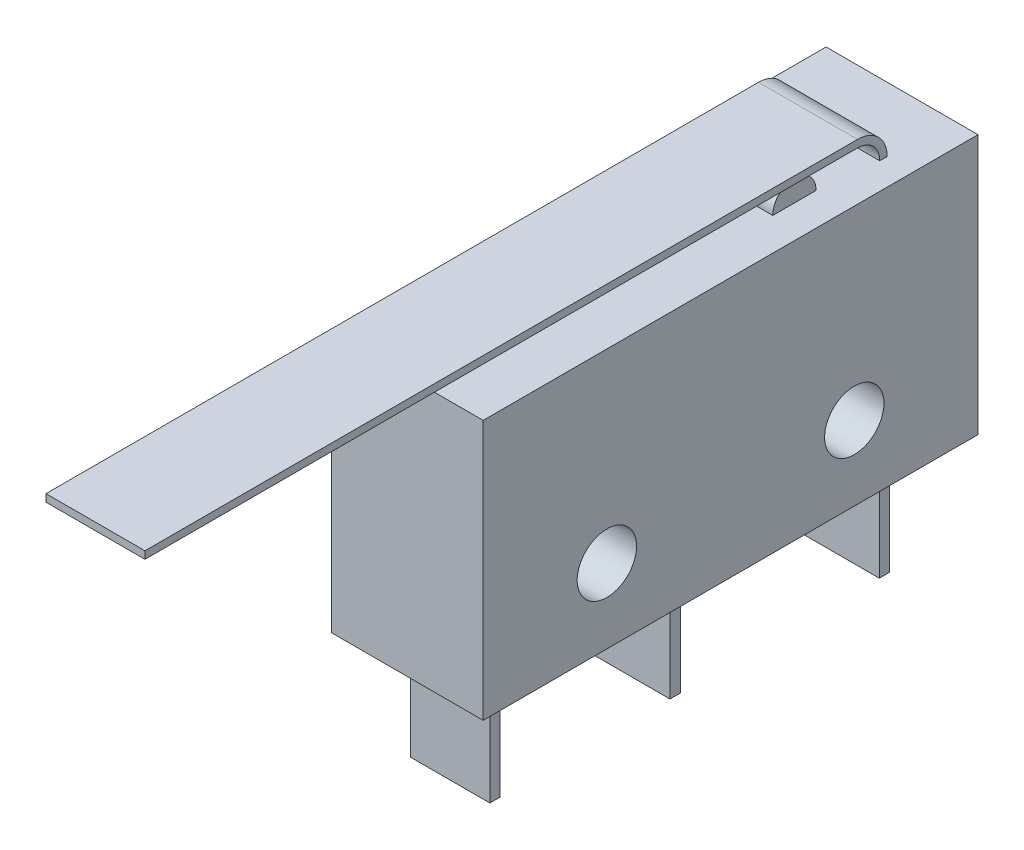
SolidWorks part; units mm, degrees
ref_plane "Front Plane" through (0, 0, 0) normal (0, 0, 1) x (1, 0, 0)
ref_plane "Top Plane" through (0, 0, 0) normal (0, 1, 0) x (1, 0, 0)
ref_plane "Right Plane" through (0, 0, 0) normal (1, 0, 0) x (0, 0, -1)
sketch "Sketch1" plane through (0, 0, 0) normal (1, 0, 0) x (0, 0, -1)
  line L1 (0, 0) -> (20, 0)
  line L2 (0, 0) -> (0, -10.5)
  line L3 (0, -10.5) -> (20, -10.5)
  line L4 (20, 0) -> (20, -10.5)
  circle A0 centre (5, -7.5) radius 1.2
  circle A1 centre (15, -7.5) radius 1.2
  circle A2 centre (5, -7.5) radius 1.2 construction
  circle A3 centre (15, -7.5) radius 1.2 construction
extrude "Boss-Extrude1" add sketch "Sketch1" along normal blind 6.14
ref_plane "Midplane" through (3.07, 0, 0) normal (1, 0, 0) x (0, 0, -1)
sketch "Sketch2" plane through (3.07, 0, 0) normal (1, 0, 0) x (0, 0, -1)
  line L1 (16.2, 0.9) -> (-12.6, 0.9)
  line L2 (-12.6, 0.9) -> (-12.6, 1.2)
  line L3 (-45.2837, 1.2) -> (16.2, 1.2) construction
  line L4 (-12.6, 1.2) -> (16.2, 1.2)
  line L5 (17.4, 0) -> (17.1, 0)
  line L6 (20, 0) -> (0, 0) construction
  arc A0 (17.4, 0) -> (15, 0) centre (16.2, 0) ccw construction
  arc A1 (16.2, 1.2) -> (17.4, 0) centre (16.2, 0) cw
  arc A2 (16.2, 0.9) -> (17.1, 0) centre (16.2, 0) cw
  dimension "D1" = 0.3
  dimension "D2" = 30
extrude "Boss-Extrude2" add sketch "Sketch2" along normal mid plane 4
sketch "Sketch3" plane through (3.07, 0, 0) normal (1, 0, 0) x (0, 0, -1)
  line L0 (20, 0) -> (0, 0) construction
  line L2 (-12.6, 0.9) -> (16.2, 0.9) construction
  line L3 (20, -10.5) -> (20, 0) construction
  line L5 (13.025, 0) -> (14.775, 0)
  arc A0 (13, 0) -> (14.8, 0) centre (13.9, 0) cw construction
  arc A1 (13.025, 0) -> (14.775, 0) centre (13.9, 0) cw
  dimension "D1" = 7
  dimension "D2" = 0.025
extrude "Boss-Extrude5" add sketch "Sketch3" along normal mid plane 3.5
sketch "Sketch4" plane through (3.07, 0, 0) normal (1, 0, 0) x (0, 0, -1)
  line L0 (0, -10.5) -> (20, -10.5) construction
  line L1 (2.16, -10.5) -> (1.74, -10.5)
  line L2 (2.16, -10.5) -> (2.16, -15)
  line L3 (2.16, -15) -> (1.74, -15)
  line L4 (1.74, -10.5) -> (1.74, -15)
  line L5 (1.74, -15) -> (9.02, -15) construction
  line L6 (9.02, -10.5) -> (9.44, -10.5)
  line L7 (9.02, -10.5) -> (9.02, -15)
  line L8 (9.02, -15) -> (9.44, -15)
  line L9 (9.44, -10.5) -> (9.44, -15)
  line L10 (17.48, -10.5) -> (17.9, -10.5)
  line L11 (17.48, -10.5) -> (17.48, -15)
  line L12 (17.48, -15) -> (17.9, -15)
  line L13 (17.9, -10.5) -> (17.9, -15)
  line L14 (9.44, -15) -> (17.48, -15) construction
  dimension "D1" = 4.5
  dimension "D2" = 2.16
  dimension "D3" = 9.44
  dimension "D4" = 17.9
  dimension "D5" = 0.42
extrude "Boss-Extrude6" add sketch "Sketch4" along normal mid plane 3.2
